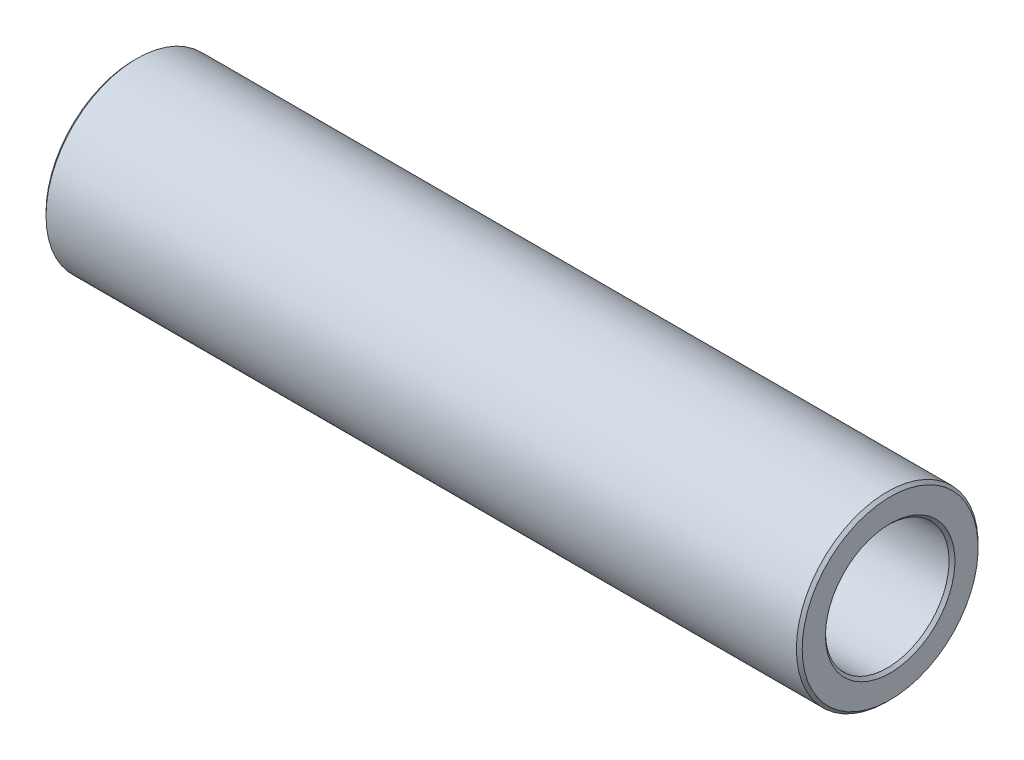
SolidWorks part; units mm, degrees
ref_plane "正面" through (0, 0, 0) normal (0, 0, 1) x (1, 0, 0)
ref_plane "平面" through (0, 0, 0) normal (0, 1, 0) x (1, 0, 0)
ref_plane "右側面" through (0, 0, 0) normal (1, 0, 0) x (0, 0, -1)
ref_plane "平面1" through (0, 0, 0) normal (0, 0, 1) x (1, 0, 0)
sketch "ｽｹｯﾁ1" plane through (0, 0, 0) normal (0, 0, 1) x (1, 0, 0)
  line L0 (0, 0) -> (0, 6.25)
  line L1 (0, 6.25) -> (52, 6.25)
  line L2 (52, 6.25) -> (52, 0)
  line L3 (52, 0) -> (0, 0)
  line L4 (500, 0) -> (-500, 0) construction
revolve "回転1" add sketch "ｽｹｯﾁ1" angle 360 about L4
ref_plane "平面2" through (0, 0, 0) normal (0, 0, 1) x (1, 0, 0)
sketch "ｽｹｯﾁ2" plane through (0, 0, 0) normal (0, 0, 1) x (1, 0, 0)
  line L0 (51.8, 6.25) -> (52, 6.05)
  line L1 (52, 6.05) -> (52, 6.25)
  line L2 (52, 6.25) -> (51.8, 6.25)
  line L3 (104, 0) -> (-104, 0) construction
revolve "ｶｯﾄ - 回転1" cut sketch "ｽｹｯﾁ2" angle 360 about L3
ref_plane "平面3" through (0, 0, 0) normal (0, 0, 1) x (1, 0, 0)
sketch "ｽｹｯﾁ3" plane through (0, 0, 0) normal (0, 0, 1) x (1, 0, 0)
  line L0 (0, 6.25) -> (0, 6.05)
  line L1 (0, 6.05) -> (0.2, 6.25)
  line L2 (0.2, 6.25) -> (0, 6.25)
  line L3 (104, 0) -> (-104, 0) construction
revolve "ｶｯﾄ - 回転2" cut sketch "ｽｹｯﾁ3" angle 360 about L3
ref_plane "平面4" through (0, 0, 0) normal (0, 0, 1) x (1, 0, 0)
sketch "ｽｹｯﾁ4" plane through (0, 0, 0) normal (0, 0, 1) x (1, 0, 0)
  line L0 (0, 0) -> (0, 4.25)
  line L1 (0, 4.25) -> (52, 4.25)
  line L2 (52, 4.25) -> (52, 0)
  line L3 (52, 0) -> (0, 0)
  line L4 (25, 0) -> (-25, 0) construction
revolve "ｶｯﾄ - 回転3" cut sketch "ｽｹｯﾁ4" angle 360 about L4
ref_plane "平面5" through (0, 0, 0) normal (0, 0, 1) x (1, 0, 0)
sketch "ｽｹｯﾁ5" plane through (0, 0, 0) normal (0, 0, 1) x (1, 0, 0)
  line L0 (0, 4.45) -> (0, 4.25)
  line L1 (0, 4.25) -> (0.2, 4.25)
  line L2 (0.2, 4.25) -> (0, 4.45)
  line L3 (25, 0) -> (-25, 0) construction
revolve "ｶｯﾄ - 回転4" cut sketch "ｽｹｯﾁ5" angle 360 about L3
ref_plane "平面6" through (0, 0, 0) normal (0, 0, 1) x (1, 0, 0)
sketch "ｽｹｯﾁ6" plane through (0, 0, 0) normal (0, 0, 1) x (1, 0, 0)
  line L0 (51.8, 4.25) -> (52, 4.25)
  line L1 (52, 4.25) -> (52, 4.45)
  line L2 (52, 4.45) -> (51.8, 4.25)
  line L3 (25, 0) -> (-25, 0) construction
revolve "ｶｯﾄ - 回転5" cut sketch "ｽｹｯﾁ6" angle 360 about L3
